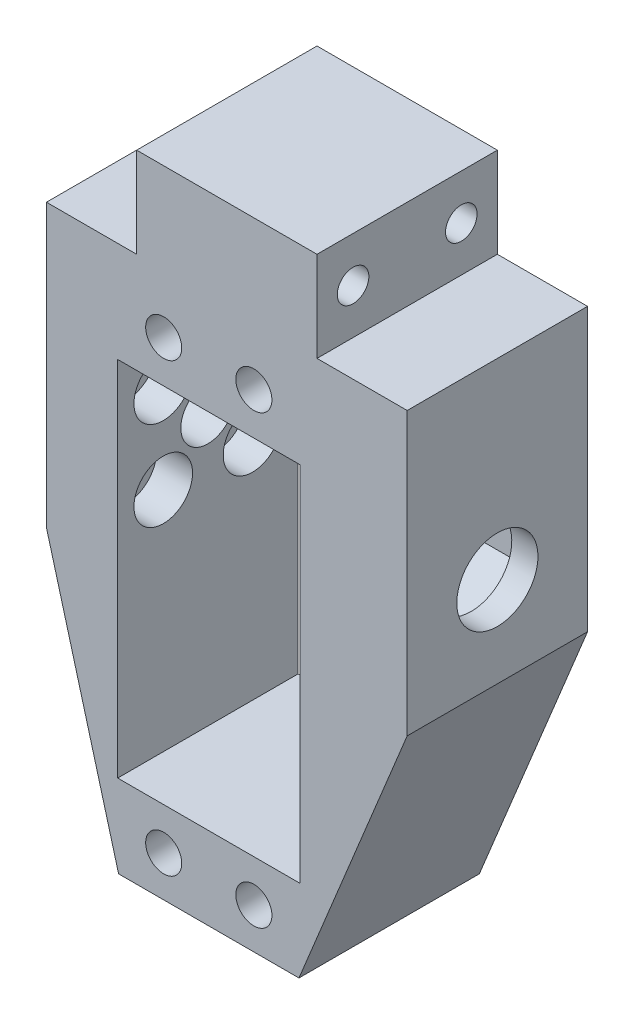
SolidWorks part; units mm, degrees
ref_plane "Top Plane" through (0, 0, 0) normal (0, 0, 1) x (1, 0, 0)
ref_plane "Right Plane" through (0, 0, 0) normal (0, 1, 0) x (1, 0, 0)
ref_plane "Front Plane" through (0, 0, 0) normal (1, 0, 0) x (0, 0, -1)
sketch "Sketch1" plane through (0, 0, 0) normal (0, 0, 1) x (1, 0, 0)
  line L0 (0, 10) -> (0, -30) construction
  line L1 (-10, 10) -> (10, 10) construction
  line L2 (-10, 10) -> (-10, -30) construction
  line L3 (-10, -30) -> (10, -30) construction
  line L4 (10, 10) -> (10, -30) construction
  line L5 (-10, -10) -> (10, -10) construction
  line L6 (-10, -30) -> (-10, -37.25) construction
  line L7 (-10, -37.25) -> (10, -37.25) construction
  line L8 (10, -37.25) -> (10, -30) construction
  line L9 (10, 17.25) -> (10, 10) construction
  line L10 (-10, 17.25) -> (10, 17.25) construction
  line L11 (-10, 10) -> (-10, 17.25) construction
  line L13 (-18, 31.25) -> (22, 31.25)
  line L14 (-18, 31.25) -> (-18, -39.25)
  line L15 (-18, -39.25) -> (22, -39.25)
  line L16 (22, 31.25) -> (22, -39.25)
  circle A0 centre (0, 0) radius 15 construction
  circle A1 centre (0, 0) radius 11 construction
  circle A2 centre (0, 0) radius 4 construction
  circle A3 centre (-5, -34.75) radius 2 construction
  circle A4 centre (5, -34.75) radius 2 construction
  circle A5 centre (-5, 14.75) radius 2 construction
  circle A6 centre (5, 14.75) radius 2 construction
  dimension "D1" = 30
  dimension "D2" = 22
  dimension "D3" = 8
  dimension "D8" = 10
  dimension "D10" = 4
  dimension "D4" = 30
  dimension "D5" = 20
  dimension "D6" = 40
  dimension "D7" = 54.5
  dimension "D9" = 49.5
  dimension "D11" = 8
  dimension "D12" = 12
  dimension "D13" = 14
  dimension "D14" = 2
extrude "Boss-Extrude1" add sketch "Sketch1" against normal blind 20
sketch "Sketch2" plane through (0, 0, 0) normal (0, 0, 1) x (1, 0, 0)
  line L12 (-10.1, 10.1) -> (-10.1, -30.1)
  line L13 (-10.1, -30.1) -> (10.1, -30.1)
  line L14 (10.1, -30.1) -> (10.1, 10.1)
  line L15 (10.1, 10.1) -> (-10.1, 10.1)
  line L16 (-10.1, 10.1) -> (-10.1, -30.1)
  line L17 (-10.1, -30.1) -> (10.1, -30.1)
  line L18 (10.1, -30.1) -> (10.1, 10.1)
  line L19 (10.1, 10.1) -> (-10.1, 10.1)
  dimension "D1" = 0.1
extrude "Cut-Extrude1" cut sketch "Sketch2" against normal blind 30
sketch "Sketch3" plane through (0, 0, 0) normal (1, 0, 0) x (0, 0, -1)
  line L0 (-7.8565, 0) -> (40.9526, 0) construction
sketch "Sketch18" plane through (-18, 0, 0) normal (-1, 0, 0) x (0, 0, 1)
  line L0 (7.8565, 0) -> (-40.9526, 0) construction
  line L1 (-20, 0) -> (0, 0) construction
  line L2 (-20, 31.25) -> (-20, -39.25) construction
  line L3 (-14.9497, 4.9497) -> (-10, 0) construction
  line L4 (-10, 0) -> (-10, 7) construction
  line L5 (0, 31.25) -> (0, -39.25) construction
  circle A0 centre (-10, 0) radius 10 construction
  circle A1 centre (-10, 0) radius 7 construction
  circle A2 centre (-14.9497, 4.9497) radius 1.5 construction
  circle A3 centre (-5.0503, 4.9497) radius 1.5 construction
  circle A4 centre (-5.0503, -4.9497) radius 1.5 construction
  circle A5 centre (-14.9497, -4.9497) radius 1.5 construction
  point P13 (0, 0)
  point P22 (-10, 0)
  dimension "D1" = 20
  dimension "D2" = 14
  dimension "D3" = 45
  dimension "D4" = 3
  dimension "D6" = 10
  dimension "D5" = 4
hole_wizard "CBORE for M3 Hex Socket Head Cap Screw1" positions "Sketch5" profile "Sketch6" counterbore size "M3" standard "ISO"
sketch "Sketch5" plane through (-10.1, 0, 0) normal (1, 0, 0) x (0, 0, -1)
  point P0 (5.0503, 4.9497)
  point P3 (14.9497, 4.9497)
  point P6 (14.9497, -4.9497)
  point P9 (5.0503, -4.9497)
sketch "Sketch6" plane through (-10.1, 4.9497, -5.0503) normal (0, 1, 0) x (0, 0, -1)
  line L0 (0, 0) -> (0, 7.9)
  line L1 (0, 7.9) -> (1.6, 7.9)
  line L3 (1.6, 7.9) -> (1.6, 4)
  line L4 (1.6, 4) -> (3.25, 4)
  line L5 (3.25, 4) -> (3.25, 0)
  line L7 (3.25, 0) -> (0, 0)
  line L11 (0, -6.35) -> (0, 107.95) construction
  dimension "Thru Hole Dia." = 3.2
  dimension "Thru Hole Depth" = 7.9
  dimension "C'Bore Dia." = 6.5
  dimension "C'Bore Depth" = 4
sketch "Sketch7" plane through (10.1, 0, 0) normal (-1, 0, 0) x (0, 0, 1)
  line L0 (-10, 7.7942) -> (-10, 0) construction
  line L1 (-10, 7.7942) -> (-16.75, 3.8971)
  line L2 (-16.75, 3.8971) -> (-16.75, -3.8971)
  line L3 (-16.75, -3.8971) -> (-10, -7.7942)
  line L4 (-10, -7.7942) -> (-3.25, -3.8971)
  line L5 (-3.25, -3.8971) -> (-3.25, 3.8971)
  line L6 (-3.25, 3.8971) -> (-10, 7.7942)
  circle A0 centre (-10, 0) radius 6.75 construction
  dimension "D1" = 13.5
extrude "Cut-Extrude2" cut sketch "Sketch7" against normal blind 9
sketch "Sketch8" plane through (19.1, 0, 0) normal (-1, 0, 0) x (0, 0, 1)
  circle A0 centre (-10, 0) radius 4.5
  dimension "D1" = 9
extrude "Cut-Extrude3" cut sketch "Sketch8" against normal through all
sketch "Sketch9" plane through (0, 0, 0) normal (0, 0, 1) x (1, 0, 0)
  line L0 (-18, -10) -> (-10, -39.25)
  line L1 (-18, 31.25) -> (-18, -39.25) construction
  line L2 (-18, -39.25) -> (22, -39.25) construction
  line L3 (-10, -39.25) -> (-18, -39.25)
  line L4 (-18, -39.25) -> (-18, -10)
  line L5 (10, -39.25) -> (22, -10)
  line L6 (22, -10) -> (22, -39.25)
  line L7 (22, -39.25) -> (10, -39.25)
  line L8 (-10, -30) -> (-10, -37.25) construction
  line L9 (10, -37.25) -> (10, -30) construction
  line L10 (22, 31.25) -> (22, -39.25) construction
  dimension "D1" = 10
  dimension "D2" = 10
extrude "Cut-Extrude4" cut sketch "Sketch9" against normal through all both and the other way through all
sketch "Sketch12" plane through (0, 0, 0) normal (0, 0, 1) x (1, 0, 0)
  circle A0 centre (-5, -34.75) radius 2 construction
  circle A1 centre (5, -34.75) radius 2 construction
  circle A2 centre (5, 14.75) radius 2 construction
  circle A3 centre (-5, 14.75) radius 2 construction
  circle A48 centre (-5, -34.75) radius 2
  circle A49 centre (5, -34.75) radius 2
  circle A50 centre (5, 14.75) radius 2
  circle A51 centre (-5, 14.75) radius 2
extrude "Cut-Extrude5" cut sketch "Sketch12" against normal through all
sketch "Sketch13" plane through (0, 0, -20) normal (0, 0, -1) x (-1, 0, 0)
  line L0 (-8.4641, 14.75) -> (-1.5359, 14.75) construction
  line L1 (-1.5359, 14.75) -> (-3.2679, 17.75)
  line L2 (-3.2679, 17.75) -> (-6.7321, 17.75)
  line L3 (-6.7321, 17.75) -> (-8.4641, 14.75)
  line L4 (-8.4641, 14.75) -> (-6.7321, 11.75)
  line L5 (-6.7321, 11.75) -> (-3.2679, 11.75)
  line L6 (-3.2679, 11.75) -> (-1.5359, 14.75)
  line L10 (3.2679, 17.75) -> (1.5359, 14.75)
  line L11 (1.5359, 14.75) -> (3.2679, 11.75)
  line L12 (3.2679, 11.75) -> (6.7321, 11.75)
  line L13 (6.7321, 11.75) -> (8.4641, 14.75)
  line L14 (8.4641, 14.75) -> (6.7321, 17.75)
  line L15 (6.7321, 17.75) -> (3.2679, 17.75)
  line L16 (-6.7321, -31.75) -> (-8.4641, -34.75)
  line L17 (-8.4641, -34.75) -> (-6.7321, -37.75)
  line L18 (-6.7321, -37.75) -> (-3.2679, -37.75)
  line L19 (-3.2679, -37.75) -> (-1.5359, -34.75)
  line L20 (-1.5359, -34.75) -> (-3.2679, -31.75)
  line L21 (-3.2679, -31.75) -> (-6.7321, -31.75)
  line L22 (3.2679, -31.75) -> (1.5359, -34.75)
  line L23 (1.5359, -34.75) -> (3.2679, -37.75)
  line L24 (3.2679, -37.75) -> (6.7321, -37.75)
  line L25 (6.7321, -37.75) -> (8.4641, -34.75)
  line L26 (8.4641, -34.75) -> (6.7321, -31.75)
  line L27 (6.7321, -31.75) -> (3.2679, -31.75)
  circle A0 centre (-5, 14.75) radius 3 construction
  circle A1 centre (5, 14.75) radius 3 construction
  circle A2 centre (-5, -34.75) radius 3 construction
  circle A3 centre (5, -34.75) radius 3 construction
  dimension "D1" = 6
extrude "Cut-Extrude6" cut sketch "Sketch13" against normal offset from surface (16 mm away) 4 up to face at (7, -34.75, 0)
sketch "Sketch15" plane through (0, 0, 0) normal (0, 0, 1) x (1, 0, 0)
  line L0 (-18, 31.25) -> (22, 31.25) construction
  line L1 (-18, 31.25) -> (-8, 31.25)
  line L2 (-18, 31.25) -> (-18, 21.25)
  line L3 (-18, 21.25) -> (-8, 21.25)
  line L4 (-8, 31.25) -> (-8, 21.25)
  line L5 (12, 31.25) -> (22, 31.25)
  line L6 (12, 31.25) -> (12, 21.25)
  line L7 (12, 21.25) -> (22, 21.25)
  line L8 (22, 31.25) -> (22, 21.25)
  line L9 (22, 31.25) -> (22, -39.25) construction
  line L10 (-8, 26.25) -> (12, 26.25) construction
  line L11 (2, 31.25) -> (2, 26.25) construction
  line L12 (-8, 28) -> (12, 28) construction
  line L13 (-8, 24.5) -> (12, 24.5) construction
  dimension "D1" = 10
  dimension "D2" = 20
  dimension "D3" = 10
  dimension "D4" = 10
  dimension "D5" = 3.5
extrude "Cut-Extrude7" cut sketch "Sketch15" against normal through all
sketch "Sketch16" plane through (-8, 0, 0) normal (-1, 0, 0) x (0, 0, 1)
  line L0 (-20, 26.25) -> (0, 26.25) construction
  line L1 (-20, 21.25) -> (-20, 31.25) construction
  line L2 (0, 31.25) -> (0, -39.25) construction
  line L3 (-10, 26.25) -> (-10, 31.25) construction
  line L4 (-20, 31.25) -> (0, 31.25) construction
  circle A0 centre (-16, 26.25) radius 1.75
  circle A1 centre (-4, 26.25) radius 1.75
  dimension "D1" = 12
  dimension "D2" = 3.5
extrude "Cut-Extrude8" cut sketch "Sketch16" against normal through all
sketch "Sketch17" plane through (-18, 0, 0) normal (-1, 0, 0) x (0, 0, 1)
  circle A0 centre (-10, 0) radius 3
  dimension "D1" = 6
extrude "Cut-Extrude9" cut sketch "Sketch17" against normal up to next
